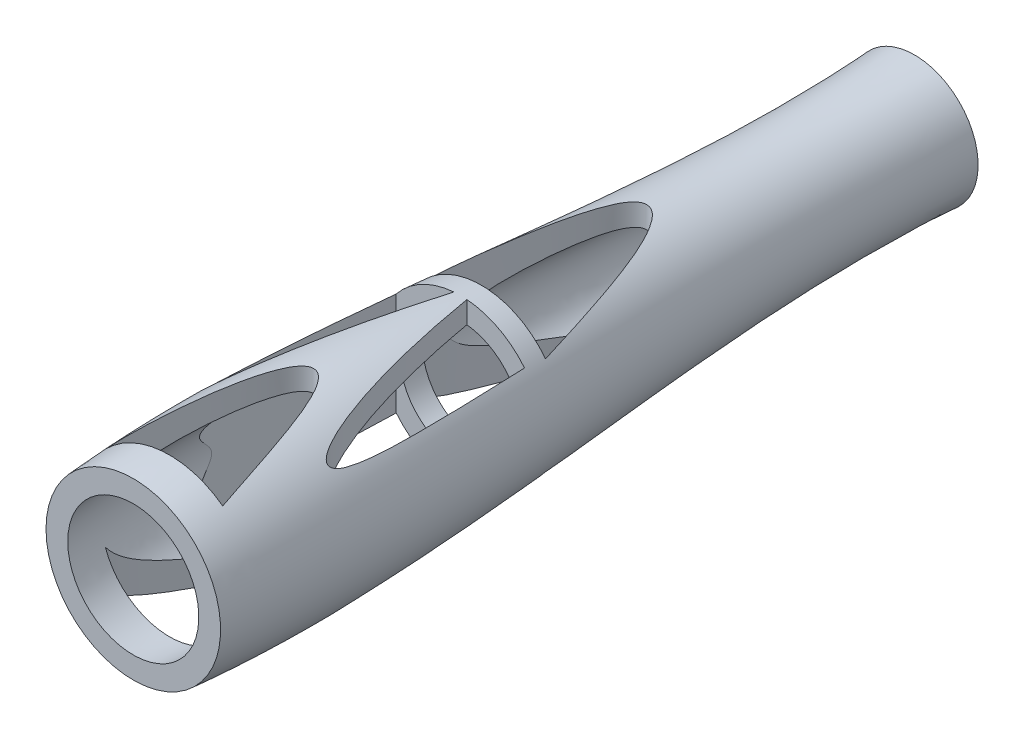
SolidWorks part; units mm, degrees
ref_plane "Front Plane" through (0, 0, 0) normal (0, 0, 1) x (1, 0, 0)
ref_plane "Top Plane" through (0, 0, 0) normal (0, 1, 0) x (1, 0, 0)
ref_plane "Right Plane" through (0, 0, 0) normal (1, 0, 0) x (0, 0, -1)
other "Graphic1"
other "Graphic (Closed) -1"
sketch "Sketch1" plane through (0, 0, 0) normal (0, 1, 0) x (1, 0, 0)
  line L0 (0, 0.2177) -> (0, -0.0611) construction
  line L1 (0, 0) -> (0.0201, 0)
  line L2 (0.0146, 0.18) -> (0, 0.18)
  line L3 (0, 0) -> (0, 0.18)
  spline S0 degree 3 poles (0.0201, 0) (0.0248, 0.0603) (0.0111, 0.1198) (0.0146, 0.18) knots 0 0 0 0 1 1 1 1
revolve "Revolve1" add sketch "Sketch1" angle 360 about L0
shell "Shell1" thickness 0.005
sketch "Sketch2" plane through (0, 0, 0) normal (0, 1, 0) x (1, 0, 0)
  line L0 (-0.0148, 0.0083) -> (0.0123, 0.0083)
  line L1 (-0.0148, 0.0754) -> (-0.0015, 0.0754)
  line L3 (0, -0.0247) -> (0, 0.0247) construction
  line L4 (0.0148, 0.0754) -> (0.0015, 0.0754)
  line L5 (-0.0148, 0.0802) -> (0.0148, 0.0802)
  spline S0 degree 3 poles (-0.0148, 0.0083) (-0.0094, 0.0196) (-0.0015, 0.0781) (0.0123, 0.0083) knots 0 0 0 0 1 1 1 1
  spline S1 degree 2 poles (-0.0015, 0.0754) (-0.0211, -0.0152) (-0.0148, 0.0754) knots 0 0 0 1 1 1
  spline S2 degree 2 poles (0.0015, 0.0754) (0.0211, -0.0152) (0.0148, 0.0754) knots 0 0 0 1 1 1
  spline S3 degree 3 poles (-0.0148, 0.0802) (-0.0098, 0.0931) (-0.0015, 0.159) (0.0148, 0.0802) knots 0 0 0 0 1 1 1 1
  point P7 (0.002, 0.0754)
extrude "Cut-Extrude1" cut sketch "Sketch2" against normal blind 0.05 and the other way blind 10
